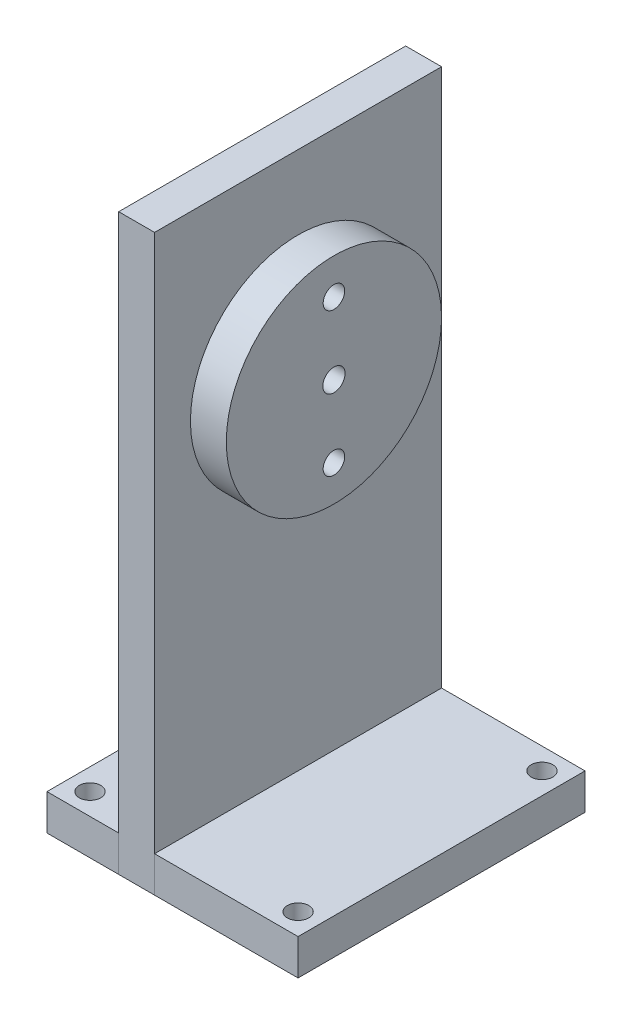
SolidWorks part; units mm, degrees
ref_plane "Front Plane" through (0, 0, 0) normal (0, 0, 1) x (1, 0, 0)
ref_plane "Top Plane" through (0, 0, 0) normal (0, 1, 0) x (1, 0, 0)
ref_plane "Right Plane" through (0, 0, 0) normal (1, 0, 0) x (0, 0, -1)
sketch "Sketch1" plane through (0, 0, 0) normal (1, 0, 0) x (0, 0, -1)
  line L1 (0, 0) -> (-20, 0)
  line L2 (-20, 0) -> (-20, 80)
  line L3 (-20, 80) -> (20, 80)
  line L4 (20, 80) -> (20, 0)
  line L5 (20, 0) -> (0, 0)
  circle A0 centre (0, 54.7) radius 1.2
  dimension "D2" = 2.4
  dimension "D1" = 54.7
  dimension "D3" = 20
  dimension "D4" = 80
  dimension "D5" = 40
extrude "Boss-Extrude1" add sketch "Sketch1" along normal blind 5
sketch "Sketch2" plane through (0, 0, 0) normal (0, -1, 0) x (1, 0, 0)
  line L0 (5, 20) -> (5, -20)
  line L1 (5, 0) -> (0, 0)
  line L2 (0, 20) -> (0, -20) construction
  point P9 (5, 0)
  point P10 (0, 0)
sketch "Sketch4" plane through (0, 0, 0) normal (0, -1, 0) x (1, 0, 0)
  line L0 (5, 20) -> (25, 20)
  line L1 (25, 20) -> (25, -20)
  line L2 (5, -20) -> (25, -20)
  line L3 (5, -20) -> (-10, -20)
  line L4 (-10, -20) -> (-10, 20)
  line L5 (-10, 20) -> (5, 20)
  line L6 (0, 7) -> (0, -7)
  line L7 (0, 7) -> (5, 7)
  line L8 (5, 20) -> (5, -20) construction
  line L9 (0, -7) -> (5, -7)
  line L10 (5, -7) -> (5, 7)
  circle A0 centre (-7, 17) radius 1.5
  circle A1 centre (-7, -17) radius 1.5
  circle A2 centre (22, -17) radius 1.5
  circle A3 centre (22, 17) radius 1.5
  dimension "D3" = 3
  dimension "D1" = 15
  dimension "D2" = 20
  dimension "D4" = 3
  dimension "D5" = 3
  dimension "D6" = 13
  dimension "D7" = 13
extrude "Boss-Extrude2" add sketch "Sketch4" against normal blind 5 separate body
sketch "Sketch5" plane through (0, 0, 0) normal (-1, 0, 0) x (0, 0, 1)
  line L0 (0, 54.7) -> (-10.5, 54.7)
  dimension "D1" = 10.5
ref_plane "Plane1" through (0, 54.7, 0) normal (0, 1, 0) x (1, 0, 0)
sketch "Sketch7" plane through (0, 54.7, 0) normal (0, 1, 0) x (1, 0, 0)
  line L0 (0, 0) -> (0, 10.5)
  line L1 (0, 0) -> (0, 10.5) construction
  line L2 (0, 10.5) -> (-22.1812, 10.5)
  line L3 (-12, 10.5) -> (-1.7559, 18.5036)
  line L4 (-12, 10.5) -> (-15.9401, 7.4217)
  line L5 (-15.2628, 6.5549) -> (-1.0786, 17.6368)
  line L6 (-14.0315, 4.9789) -> (0.1527, 16.0608)
  line L7 (-15.9401, 7.4217) -> (-14.0315, 4.9789)
  line L8 (-1.7559, 18.5036) -> (0.1527, 16.0608)
  line L9 (-12, 10.5) -> (-323.7451, 10.5)
  line L10 (-12, 10.5) -> (-23.5995, 25.3466)
  line L11 (-12, 10.5) -> (63.418, 312.985)
  dimension "D1" = 38
  dimension "D2" = 1.1
  dimension "D3" = 2
  dimension "D4" = 10.5
  dimension "D5" = 5
  dimension "D6" = 12
  dimension "D7" = 13
sketch "Sketch8" plane through (0, 54.7, 0) normal (0, 1, 0) x (1, 0, 0)
  line L0 (-14.0315, 4.9789) -> (0, 4.9789)
  line L1 (0, 0) -> (0, 10.5) construction
  line L2 (0, 9.2277) -> (0, 15.9415)
  line L3 (0, 4.9789) -> (0, 0)
  line L4 (-14.0315, 4.9789) -> (0, 15.9415)
  line L5 (0, 0) -> (2.0786, 0)
  line L6 (5, 0) -> (0, 0) construction
  line L7 (2.0786, 0) -> (2.0786, 9.2277)
  line L8 (2.0786, 9.2277) -> (0, 9.2277)
extrude "Boss-Extrude3" add sketch "Sketch8" along normal blind 5 and the other way blind 5 separate body
sketch "Sketch10" plane through (5, 0, 0) normal (1, 0, 0) x (0, 0, -1)
  circle A0 centre (0, 54.7) radius 1.55
  circle A1 centre (0, 64.7) radius 1.5
  circle A2 centre (0, 44.7) radius 1.5
  circle A3 centre (0, 54.7) radius 15
  dimension "D1" = 3.1
  dimension "D2" = 3
  dimension "D4" = 30
  dimension "D3" = 10
extrude "Boss-Extrude5" add sketch "Sketch10" along normal blind 5 separate body
sketch "Sketch12" plane through (-7.734, 0, -9.899) normal (-0.6157, 0, -0.788) x (-0.788, 0, 0.6157)
  line L0 (-9.8145, 59.7) -> (7.9917, 59.7)
  line L1 (7.9917, 59.7) -> (7.9917, 49.7)
  line L2 (7.9917, 49.7) -> (-9.8145, 49.7)
  line L3 (-9.8145, 49.7) -> (-9.8145, 59.7)
extrude "Boss-Extrude6" add sketch "Sketch12" along normal blind 2 separate body
